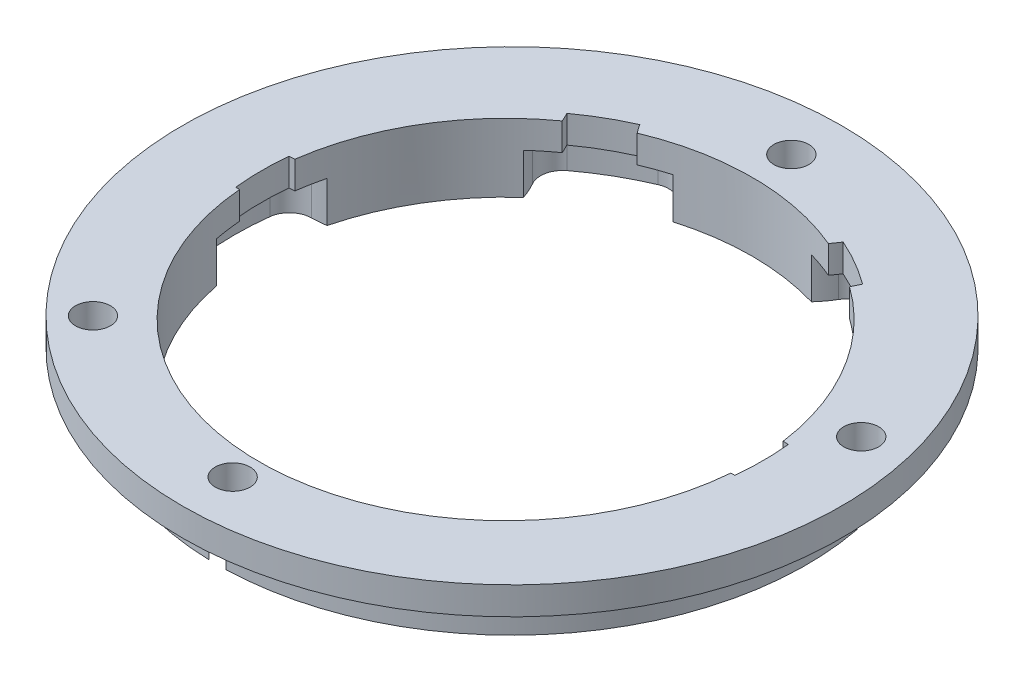
SolidWorks part; units mm, degrees
ref_plane "Front Plane" through (0, 0, 0) normal (0, 0, 1) x (1, 0, 0)
ref_plane "Top Plane" through (0, 0, 0) normal (0, 1, 0) x (1, 0, 0)
ref_plane "Right Plane" through (0, 0, 0) normal (1, 0, 0) x (0, 0, -1)
sketch "Sketch1" plane through (0, 0, 0) normal (0, 1, 0) x (1, 0, 0)
  circle A0 centre (0, 0) radius 31.75 construction
  arc A1 (-10.16, 30.0805) -> (10.16, 30.0805) centre (0, 33.6183) ccw
  arc A2 (20.9705, 23.8391) -> (31.1305, 6.2414) centre (29.1143, 16.8092) ccw
  arc A3 (31.1305, -6.2414) -> (20.9705, -23.8391) centre (29.1143, -16.8092) ccw
  arc A4 (10.16, -30.0805) -> (-10.16, -30.0805) centre (0, -33.6183) ccw
  arc A5 (-20.9705, -23.8391) -> (-31.1305, -6.2414) centre (-29.1143, -16.8092) ccw
  arc A6 (-31.1305, 6.2414) -> (-20.9705, 23.8391) centre (-29.1143, 16.8092) ccw
  arc A7 (-20.9705, 23.8391) -> (-10.16, 30.0805) centre (0, 0) cw
  arc A8 (10.16, 30.0805) -> (20.9705, 23.8391) centre (0, 0) cw
  arc A9 (31.1305, 6.2414) -> (31.1305, -6.2414) centre (0, 0) cw
  arc A10 (20.9705, -23.8391) -> (10.16, -30.0805) centre (0, 0) cw
  arc A11 (-10.16, -30.0805) -> (-20.9705, -23.8391) centre (0, 0) cw
  arc A12 (-31.1305, -6.2414) -> (-31.1305, 6.2414) centre (0, 0) cw
  circle A13 centre (0, 0) radius 6.35
  point P24 (0, 0)
  dimension "D1" = 63.5
  dimension "D3" = 8.89
  dimension "D5" = 12.7
  dimension "D2" = 20.32
  dimension "D4" = 6
extrude "Boss-Extrude1" add sketch "Sketch1" along normal blind 9.652
fillet "Fillet1" radius 2.54 12 edges at (20.9705, 4.826, 23.8391) (31.1305, 4.826, 6.2414) (31.1305, 4.826, -6.2414) (20.9705, 4.826, -23.8391) (10.16, 4.826, -30.0805) (-10.16, 4.826, -30.0805) (-20.9705, 4.826, -23.8391) (-31.1305, 4.826, -6.2414) (-31.1305, 4.826, 6.2414) (-20.9705, 4.826, 23.8391) (10.16, 4.826, 30.0805) (-10.16, 4.826, 30.0805)
sketch "Sketch2" plane through (0, 0, 0) normal (0, -1, 0) x (1, 0, 0)
  circle A0 centre (0, 0) radius 33.75
  arc A24 (19.7507, 22.1068) -> (29.0204, 6.0512) centre (29.1143, 16.8092) ccw
  arc A25 (19.7507, 22.1068) -> (19.0652, 25.3886) centre (17.54, 23.3575) ccw
  arc A26 (19.0652, 25.3886) -> (12.4545, 29.2053) centre (0, 0) ccw
  arc A27 (12.4545, 29.2053) -> (9.2697, 28.158) centre (11.4582, 26.8688) ccw
  arc A28 (-9.2697, 28.158) -> (9.2697, 28.158) centre (0, 33.6183) ccw
  arc A29 (-9.2697, 28.158) -> (-12.4545, 29.2053) centre (-11.4582, 26.8688) ccw
  arc A30 (-12.4545, 29.2053) -> (-19.0652, 25.3886) centre (0, 0) ccw
  arc A31 (-19.0652, 25.3886) -> (-19.7507, 22.1068) centre (-17.54, 23.3575) ccw
  arc A32 (-29.0204, 6.0512) -> (-19.7507, 22.1068) centre (-29.1143, 16.8092) ccw
  arc A33 (-29.0204, 6.0512) -> (-31.5198, 3.8167) centre (-28.9982, 3.5113) ccw
  arc A34 (-31.5198, 3.8167) -> (-31.5198, -3.8167) centre (0, 0) ccw
  arc A35 (-31.5198, -3.8167) -> (-29.0204, -6.0512) centre (-28.9982, -3.5113) ccw
  arc A36 (-19.7507, -22.1068) -> (-29.0204, -6.0512) centre (-29.1143, -16.8092) ccw
  arc A37 (-19.7507, -22.1068) -> (-19.0652, -25.3886) centre (-17.54, -23.3575) ccw
  arc A38 (-19.0652, -25.3886) -> (-12.4545, -29.2053) centre (0, 0) ccw
  arc A39 (-12.4545, -29.2053) -> (-9.2697, -28.158) centre (-11.4582, -26.8688) ccw
  arc A40 (9.2697, -28.158) -> (-9.2697, -28.158) centre (0, -33.6183) ccw
  arc A41 (9.2697, -28.158) -> (12.4545, -29.2053) centre (11.4582, -26.8688) ccw
  arc A42 (12.4545, -29.2053) -> (19.0652, -25.3886) centre (0, 0) ccw
  arc A43 (19.0652, -25.3886) -> (19.7507, -22.1068) centre (17.54, -23.3575) ccw
  arc A44 (29.0204, -6.0512) -> (19.7507, -22.1068) centre (29.1143, -16.8092) ccw
  arc A45 (29.0204, -6.0512) -> (31.5198, -3.8167) centre (28.9982, -3.5113) ccw
  arc A46 (31.5198, -3.8167) -> (31.5198, 3.8167) centre (0, 0) ccw
  arc A47 (31.5198, 3.8167) -> (29.0204, 6.0512) centre (28.9982, 3.5113) ccw
  arc A48 (19.7507, 22.1068) -> (29.0204, 6.0512) centre (29.1143, 16.8092) ccw
  arc A49 (19.7507, 22.1068) -> (19.0652, 25.3886) centre (17.54, 23.3575) ccw
  arc A50 (19.0652, 25.3886) -> (12.4545, 29.2053) centre (0, 0) ccw
  arc A51 (12.4545, 29.2053) -> (9.2697, 28.158) centre (11.4582, 26.8688) ccw
  arc A52 (-9.2697, 28.158) -> (9.2697, 28.158) centre (0, 33.6183) ccw
  arc A53 (-9.2697, 28.158) -> (-12.4545, 29.2053) centre (-11.4582, 26.8688) ccw
  arc A54 (-12.4545, 29.2053) -> (-19.0652, 25.3886) centre (0, 0) ccw
  arc A55 (-19.0652, 25.3886) -> (-19.7507, 22.1068) centre (-17.54, 23.3575) ccw
  arc A56 (-29.0204, 6.0512) -> (-19.7507, 22.1068) centre (-29.1143, 16.8092) ccw
  arc A57 (-29.0204, 6.0512) -> (-31.5198, 3.8167) centre (-28.9982, 3.5113) ccw
  arc A58 (-31.5198, 3.8167) -> (-31.5198, -3.8167) centre (0, 0) ccw
  arc A59 (-31.5198, -3.8167) -> (-29.0204, -6.0512) centre (-28.9982, -3.5113) ccw
  arc A60 (-19.7507, -22.1068) -> (-29.0204, -6.0512) centre (-29.1143, -16.8092) ccw
  arc A61 (-19.7507, -22.1068) -> (-19.0652, -25.3886) centre (-17.54, -23.3575) ccw
  arc A62 (-19.0652, -25.3886) -> (-12.4545, -29.2053) centre (0, 0) ccw
  arc A63 (-12.4545, -29.2053) -> (-9.2697, -28.158) centre (-11.4582, -26.8688) ccw
  arc A64 (9.2697, -28.158) -> (-9.2697, -28.158) centre (0, -33.6183) ccw
  arc A65 (9.2697, -28.158) -> (12.4545, -29.2053) centre (11.4582, -26.8688) ccw
  arc A66 (12.4545, -29.2053) -> (19.0652, -25.3886) centre (0, 0) ccw
  arc A67 (19.0652, -25.3886) -> (19.7507, -22.1068) centre (17.54, -23.3575) ccw
  arc A68 (29.0204, -6.0512) -> (19.7507, -22.1068) centre (29.1143, -16.8092) ccw
  arc A69 (29.0204, -6.0512) -> (31.5198, -3.8167) centre (28.9982, -3.5113) ccw
  arc A70 (31.5198, -3.8167) -> (31.5198, 3.8167) centre (0, 0) ccw
  arc A71 (31.5198, 3.8167) -> (29.0204, 6.0512) centre (28.9982, 3.5113) ccw
  dimension "D2" = 2
  dimension "D1" = 0
extrude "Boss-Extrude2" add sketch "Sketch2" against normal through all separate body
sketch "Sketch3" plane through (0, 9.652, 0) normal (0, 1, 0) x (1, 0, 0)
  arc A24 (12.4545, -29.2053) -> (19.0652, -25.3886) centre (0, 0) ccw
  arc A25 (19.0652, -25.3886) -> (19.7507, -22.1068) centre (17.54, -23.3575) ccw
  arc A26 (29.0204, -6.0512) -> (19.7507, -22.1068) centre (29.1143, -16.8092) ccw
  arc A27 (29.0204, -6.0512) -> (31.5198, -3.8167) centre (28.9982, -3.5113) ccw
  arc A28 (31.5198, -3.8167) -> (31.5198, 3.8167) centre (0, 0) ccw
  arc A29 (31.5198, 3.8167) -> (29.0204, 6.0512) centre (28.9982, 3.5113) ccw
  arc A30 (19.7507, 22.1068) -> (29.0204, 6.0512) centre (29.1143, 16.8092) ccw
  arc A31 (19.7507, 22.1068) -> (19.0652, 25.3886) centre (17.54, 23.3575) ccw
  arc A32 (19.0652, 25.3886) -> (12.4545, 29.2053) centre (0, 0) ccw
  arc A33 (12.4545, 29.2053) -> (9.2697, 28.158) centre (11.4582, 26.8688) ccw
  arc A34 (-9.2697, 28.158) -> (9.2697, 28.158) centre (0, 33.6183) ccw
  arc A35 (-9.2697, 28.158) -> (-12.4545, 29.2053) centre (-11.4582, 26.8688) ccw
  arc A36 (-12.4545, 29.2053) -> (-19.0652, 25.3886) centre (0, 0) ccw
  arc A37 (-19.0652, 25.3886) -> (-19.7507, 22.1068) centre (-17.54, 23.3575) ccw
  arc A38 (-29.0204, 6.0512) -> (-19.7507, 22.1068) centre (-29.1143, 16.8092) ccw
  arc A39 (-29.0204, 6.0512) -> (-31.5198, 3.8167) centre (-28.9982, 3.5113) ccw
  arc A40 (-31.5198, 3.8167) -> (-31.5198, -3.8167) centre (0, 0) ccw
  arc A41 (-31.5198, -3.8167) -> (-29.0204, -6.0512) centre (-28.9982, -3.5113) ccw
  arc A42 (-19.7507, -22.1068) -> (-29.0204, -6.0512) centre (-29.1143, -16.8092) ccw
  arc A43 (-19.7507, -22.1068) -> (-19.0652, -25.3886) centre (-17.54, -23.3575) ccw
  arc A44 (-19.0652, -25.3886) -> (-12.4545, -29.2053) centre (0, 0) ccw
  arc A45 (-12.4545, -29.2053) -> (-9.2697, -28.158) centre (-11.4582, -26.8688) ccw
  arc A46 (9.2697, -28.158) -> (-9.2697, -28.158) centre (0, -33.6183) ccw
  arc A47 (9.2697, -28.158) -> (12.4545, -29.2053) centre (11.4582, -26.8688) ccw
  arc A48 (12.4545, -29.2053) -> (19.0652, -25.3886) centre (0, 0) ccw
  arc A49 (19.0652, -25.3886) -> (19.7507, -22.1068) centre (17.54, -23.3575) ccw
  arc A50 (29.0204, -6.0512) -> (19.7507, -22.1068) centre (29.1143, -16.8092) ccw
  arc A51 (29.0204, -6.0512) -> (31.5198, -3.8167) centre (28.9982, -3.5113) ccw
  arc A52 (31.5198, -3.8167) -> (31.5198, 3.8167) centre (0, 0) ccw
  arc A53 (31.5198, 3.8167) -> (29.0204, 6.0512) centre (28.9982, 3.5113) ccw
  arc A54 (19.7507, 22.1068) -> (29.0204, 6.0512) centre (29.1143, 16.8092) ccw
  arc A55 (19.7507, 22.1068) -> (19.0652, 25.3886) centre (17.54, 23.3575) ccw
  arc A56 (19.0652, 25.3886) -> (12.4545, 29.2053) centre (0, 0) ccw
  arc A57 (12.4545, 29.2053) -> (9.2697, 28.158) centre (11.4582, 26.8688) ccw
  arc A58 (-9.2697, 28.158) -> (9.2697, 28.158) centre (0, 33.6183) ccw
  arc A59 (-9.2697, 28.158) -> (-12.4545, 29.2053) centre (-11.4582, 26.8688) ccw
  arc A60 (-12.4545, 29.2053) -> (-19.0652, 25.3886) centre (0, 0) ccw
  arc A61 (-19.0652, 25.3886) -> (-19.7507, 22.1068) centre (-17.54, 23.3575) ccw
  arc A62 (-29.0204, 6.0512) -> (-19.7507, 22.1068) centre (-29.1143, 16.8092) ccw
  arc A63 (-29.0204, 6.0512) -> (-31.5198, 3.8167) centre (-28.9982, 3.5113) ccw
  arc A64 (-31.5198, 3.8167) -> (-31.5198, -3.8167) centre (0, 0) ccw
  arc A65 (-31.5198, -3.8167) -> (-29.0204, -6.0512) centre (-28.9982, -3.5113) ccw
  arc A66 (-19.7507, -22.1068) -> (-29.0204, -6.0512) centre (-29.1143, -16.8092) ccw
  arc A67 (-19.7507, -22.1068) -> (-19.0652, -25.3886) centre (-17.54, -23.3575) ccw
  arc A68 (-19.0652, -25.3886) -> (-12.4545, -29.2053) centre (0, 0) ccw
  arc A69 (-12.4545, -29.2053) -> (-9.2697, -28.158) centre (-11.4582, -26.8688) ccw
  arc A70 (9.2697, -28.158) -> (-9.2697, -28.158) centre (0, -33.6183) ccw
  arc A71 (9.2697, -28.158) -> (12.4545, -29.2053) centre (11.4582, -26.8688) ccw
  dimension "D1" = 0
extrude "Cut-Extrude1" cut sketch "Sketch3" against normal through all
sketch "Sketch4" plane through (0, 9.652, 0) normal (0, 1, 0) x (1, 0, 0)
  circle A0 centre (0, 0) radius 37.75
  circle A1 centre (0, 0) radius 33.75
  circle A2 centre (0, 0) radius 33.75 construction
  arc A26 (9.2697, -28.158) -> (-9.2697, -28.158) centre (0, -33.6183) ccw
  arc A27 (9.2697, -28.158) -> (12.4545, -29.2053) centre (11.4582, -26.8688) ccw
  arc A28 (12.4545, -29.2053) -> (19.0652, -25.3886) centre (0, 0) ccw
  arc A29 (19.0652, -25.3886) -> (19.7507, -22.1068) centre (17.54, -23.3575) ccw
  arc A30 (29.0204, -6.0512) -> (19.7507, -22.1068) centre (29.1143, -16.8092) ccw
  arc A31 (29.0204, -6.0512) -> (31.5198, -3.8167) centre (28.9982, -3.5113) ccw
  arc A32 (31.5198, -3.8167) -> (31.5198, 3.8167) centre (0, 0) ccw
  arc A33 (31.5198, 3.8167) -> (29.0204, 6.0512) centre (28.9982, 3.5113) ccw
  arc A34 (19.7507, 22.1068) -> (29.0204, 6.0512) centre (29.1143, 16.8092) ccw
  arc A35 (19.7507, 22.1068) -> (19.0652, 25.3886) centre (17.54, 23.3575) ccw
  arc A36 (19.0652, 25.3886) -> (12.4545, 29.2053) centre (0, 0) ccw
  arc A37 (12.4545, 29.2053) -> (9.2697, 28.158) centre (11.4582, 26.8688) ccw
  arc A38 (-9.2697, 28.158) -> (9.2697, 28.158) centre (0, 33.6183) ccw
  arc A39 (-9.2697, 28.158) -> (-12.4545, 29.2053) centre (-11.4582, 26.8688) ccw
  arc A40 (-12.4545, 29.2053) -> (-19.0652, 25.3886) centre (0, 0) ccw
  arc A41 (-19.0652, 25.3886) -> (-19.7507, 22.1068) centre (-17.54, 23.3575) ccw
  arc A42 (-29.0204, 6.0512) -> (-19.7507, 22.1068) centre (-29.1143, 16.8092) ccw
  arc A43 (-29.0204, 6.0512) -> (-31.5198, 3.8167) centre (-28.9982, 3.5113) ccw
  arc A44 (-31.5198, 3.8167) -> (-31.5198, -3.8167) centre (0, 0) ccw
  arc A45 (-31.5198, -3.8167) -> (-29.0204, -6.0512) centre (-28.9982, -3.5113) ccw
  arc A46 (-19.7507, -22.1068) -> (-29.0204, -6.0512) centre (-29.1143, -16.8092) ccw
  arc A47 (-19.7507, -22.1068) -> (-19.0652, -25.3886) centre (-17.54, -23.3575) ccw
  arc A48 (-19.0652, -25.3886) -> (-12.4545, -29.2053) centre (0, 0) ccw
  arc A49 (-12.4545, -29.2053) -> (-9.2697, -28.158) centre (-11.4582, -26.8688) ccw
  arc A50 (9.2697, -28.158) -> (-9.2697, -28.158) centre (0, -33.6183) ccw
  arc A51 (9.2697, -28.158) -> (12.4545, -29.2053) centre (11.4582, -26.8688) ccw
  arc A52 (12.4545, -29.2053) -> (19.0652, -25.3886) centre (0, 0) ccw
  arc A53 (19.0652, -25.3886) -> (19.7507, -22.1068) centre (17.54, -23.3575) ccw
  arc A54 (29.0204, -6.0512) -> (19.7507, -22.1068) centre (29.1143, -16.8092) ccw
  arc A55 (29.0204, -6.0512) -> (31.5198, -3.8167) centre (28.9982, -3.5113) ccw
  arc A56 (31.5198, -3.8167) -> (31.5198, 3.8167) centre (0, 0) ccw
  arc A57 (31.5198, 3.8167) -> (29.0204, 6.0512) centre (28.9982, 3.5113) ccw
  arc A58 (19.7507, 22.1068) -> (29.0204, 6.0512) centre (29.1143, 16.8092) ccw
  arc A59 (19.7507, 22.1068) -> (19.0652, 25.3886) centre (17.54, 23.3575) ccw
  arc A60 (19.0652, 25.3886) -> (12.4545, 29.2053) centre (0, 0) ccw
  arc A61 (12.4545, 29.2053) -> (9.2697, 28.158) centre (11.4582, 26.8688) ccw
  arc A62 (-9.2697, 28.158) -> (9.2697, 28.158) centre (0, 33.6183) ccw
  arc A63 (-9.2697, 28.158) -> (-12.4545, 29.2053) centre (-11.4582, 26.8688) ccw
  arc A64 (-12.4545, 29.2053) -> (-19.0652, 25.3886) centre (0, 0) ccw
  arc A65 (-19.0652, 25.3886) -> (-19.7507, 22.1068) centre (-17.54, 23.3575) ccw
  arc A66 (-29.0204, 6.0512) -> (-19.7507, 22.1068) centre (-29.1143, 16.8092) ccw
  arc A67 (-29.0204, 6.0512) -> (-31.5198, 3.8167) centre (-28.9982, 3.5113) ccw
  arc A68 (-31.5198, 3.8167) -> (-31.5198, -3.8167) centre (0, 0) ccw
  arc A69 (-31.5198, -3.8167) -> (-29.0204, -6.0512) centre (-28.9982, -3.5113) ccw
  arc A70 (-19.7507, -22.1068) -> (-29.0204, -6.0512) centre (-29.1143, -16.8092) ccw
  arc A71 (-19.7507, -22.1068) -> (-19.0652, -25.3886) centre (-17.54, -23.3575) ccw
  arc A72 (-19.0652, -25.3886) -> (-12.4545, -29.2053) centre (0, 0) ccw
  arc A73 (-12.4545, -29.2053) -> (-9.2697, -28.158) centre (-11.4582, -26.8688) ccw
  arc M27 (29.0204, -6.0512) -> (19.7507, -22.1068) centre (29.1143, -16.8092) ccw
  arc M28 (19.7507, -22.1068) -> (19.0652, -25.3886) centre (17.54, -23.3575) cw
  arc M29 (19.0652, -25.3886) -> (12.4545, -29.2053) centre (0, 0) cw
  arc M30 (12.4545, -29.2053) -> (9.2697, -28.158) centre (11.4582, -26.8688) cw
  arc M31 (9.2697, -28.158) -> (-9.2697, -28.158) centre (0, -33.6183) ccw
  arc M32 (-9.2697, -28.158) -> (-12.4545, -29.2053) centre (-11.4582, -26.8688) cw
  arc M33 (-12.4545, -29.2053) -> (-19.0652, -25.3886) centre (0, 0) cw
  arc M34 (-19.0652, -25.3886) -> (-19.7507, -22.1068) centre (-17.54, -23.3575) cw
  arc M35 (-19.7507, -22.1068) -> (-29.0204, -6.0512) centre (-29.1143, -16.8092) ccw
  arc M36 (-29.0204, -6.0512) -> (-31.5198, -3.8167) centre (-28.9982, -3.5113) cw
  arc M37 (-31.5198, -3.8167) -> (-31.5198, 3.8167) centre (0, 0) cw
  arc M38 (-31.5198, 3.8167) -> (-29.0204, 6.0512) centre (-28.9982, 3.5113) cw
  arc M39 (-29.0204, 6.0512) -> (-19.7507, 22.1068) centre (-29.1143, 16.8092) ccw
  arc M40 (-19.7507, 22.1068) -> (-19.0652, 25.3886) centre (-17.54, 23.3575) cw
  arc M41 (-19.0652, 25.3886) -> (-12.4545, 29.2053) centre (0, 0) cw
  arc M42 (-12.4545, 29.2053) -> (-9.2697, 28.158) centre (-11.4582, 26.8688) cw
  arc M43 (-9.2697, 28.158) -> (9.2697, 28.158) centre (0, 33.6183) ccw
  arc M44 (9.2697, 28.158) -> (12.4545, 29.2053) centre (11.4582, 26.8688) cw
  arc M45 (12.4545, 29.2053) -> (19.0652, 25.3886) centre (0, 0) cw
  arc M46 (19.0652, 25.3886) -> (19.7507, 22.1068) centre (17.54, 23.3575) cw
  arc M47 (19.7507, 22.1068) -> (29.0204, 6.0512) centre (29.1143, 16.8092) ccw
  arc M48 (29.0204, 6.0512) -> (31.5198, 3.8167) centre (28.9982, 3.5113) cw
  arc M49 (31.5198, 3.8167) -> (31.5198, -3.8167) centre (0, 0) cw
  arc M50 (31.5198, -3.8167) -> (29.0204, -6.0512) centre (28.9982, -3.5113) cw
  circle M51 centre (0, 0) radius 33.75
  dimension "D3" = 4
  dimension "D1" = 0
  dimension "D2" = 0
extrude "Boss-Extrude3" add sketch "Sketch4" along normal blind 3.175 contours M51 M50 M27 M28 M29 M30 M31 M32 M33 M34 M35 M36 M37 M38 M39 M40 M41 M42 M43 M44 M45 M46 M47 M48 M49 | A0 M51
sketch "Sketch9" plane through (0, 12.827, 0) normal (0, 1, 0) x (1, 0, 0)
  arc A0 (-19.0652, 25.3886) -> (-19.7507, 22.1068) centre (-17.54, 23.3575) ccw construction
  arc A1 (-29.0204, 6.0512) -> (-19.7507, 22.1068) centre (-29.1143, 16.8092) ccw construction
  arc A2 (-29.0204, 6.0512) -> (-31.5198, 3.8167) centre (-28.9982, 3.5113) ccw construction
  arc A3 (-31.5198, 3.8167) -> (-31.5198, -3.8167) centre (0, 0) ccw construction
  arc A4 (-31.5198, -3.8167) -> (-29.0204, -6.0512) centre (-28.9982, -3.5113) ccw construction
  arc A5 (-19.7507, -22.1068) -> (-29.0204, -6.0512) centre (-29.1143, -16.8092) ccw construction
  arc A6 (-19.7507, -22.1068) -> (-19.0652, -25.3886) centre (-17.54, -23.3575) ccw construction
  arc A7 (-19.0652, -25.3886) -> (-12.4545, -29.2053) centre (0, 0) ccw construction
  arc A8 (-12.4545, -29.2053) -> (-9.2697, -28.158) centre (-11.4582, -26.8688) ccw construction
  arc A9 (9.2697, -28.158) -> (-9.2697, -28.158) centre (0, -33.6183) ccw construction
  arc A10 (9.2697, -28.158) -> (12.4545, -29.2053) centre (11.4582, -26.8688) ccw construction
  arc A11 (19.0652, -25.3886) -> (19.7507, -22.1068) centre (17.54, -23.3575) ccw construction
  arc A12 (12.4545, -29.2053) -> (19.0652, -25.3886) centre (0, 0) ccw construction
  arc A13 (29.0204, -6.0512) -> (19.7507, -22.1068) centre (29.1143, -16.8092) ccw construction
  arc A14 (29.0204, -6.0512) -> (31.5198, -3.8167) centre (28.9982, -3.5113) ccw construction
  arc A15 (31.5198, -3.8167) -> (31.5198, 3.8167) centre (0, 0) ccw construction
  arc A16 (31.5198, 3.8167) -> (29.0204, 6.0512) centre (28.9982, 3.5113) ccw construction
  arc A17 (19.7507, 22.1068) -> (29.0204, 6.0512) centre (29.1143, 16.8092) ccw construction
  arc A18 (19.7507, 22.1068) -> (19.0652, 25.3886) centre (17.54, 23.3575) ccw construction
  arc A19 (19.0652, 25.3886) -> (12.4545, 29.2053) centre (0, 0) ccw construction
  arc A20 (12.4545, 29.2053) -> (9.2697, 28.158) centre (11.4582, 26.8688) ccw construction
  arc A21 (-9.2697, 28.158) -> (9.2697, 28.158) centre (0, 33.6183) ccw construction
  arc A22 (-9.2697, 28.158) -> (-12.4545, 29.2053) centre (-11.4582, 26.8688) ccw construction
  arc A23 (-12.4545, 29.2053) -> (-19.0652, 25.3886) centre (0, 0) ccw construction
  arc A24 (-19.0652, 25.3886) -> (-19.7507, 22.1068) centre (-17.54, 23.3575) ccw
  arc A25 (-29.0204, 6.0512) -> (-19.7507, 22.1068) centre (-29.1143, 16.8092) ccw
  arc A26 (-29.0204, 6.0512) -> (-31.5198, 3.8167) centre (-28.9982, 3.5113) ccw
  arc A27 (-31.5198, 3.8167) -> (-31.5198, -3.8167) centre (0, 0) ccw
  arc A28 (-31.5198, -3.8167) -> (-29.0204, -6.0512) centre (-28.9982, -3.5113) ccw
  arc A29 (-19.7507, -22.1068) -> (-29.0204, -6.0512) centre (-29.1143, -16.8092) ccw
  arc A30 (-19.7507, -22.1068) -> (-19.0652, -25.3886) centre (-17.54, -23.3575) ccw
  arc A31 (-19.0652, -25.3886) -> (-12.4545, -29.2053) centre (0, 0) ccw
  arc A32 (-12.4545, -29.2053) -> (-9.2697, -28.158) centre (-11.4582, -26.8688) ccw
  arc A33 (9.2697, -28.158) -> (-9.2697, -28.158) centre (0, -33.6183) ccw
  arc A34 (9.2697, -28.158) -> (12.4545, -29.2053) centre (11.4582, -26.8688) ccw
  arc A35 (19.0652, -25.3886) -> (19.7507, -22.1068) centre (17.54, -23.3575) ccw
  arc A36 (12.4545, -29.2053) -> (19.0652, -25.3886) centre (0, 0) ccw
  arc A37 (29.0204, -6.0512) -> (19.7507, -22.1068) centre (29.1143, -16.8092) ccw
  arc A38 (29.0204, -6.0512) -> (31.5198, -3.8167) centre (28.9982, -3.5113) ccw
  arc A39 (31.5198, -3.8167) -> (31.5198, 3.8167) centre (0, 0) ccw
  arc A40 (31.5198, 3.8167) -> (29.0204, 6.0512) centre (28.9982, 3.5113) ccw
  arc A41 (19.7507, 22.1068) -> (29.0204, 6.0512) centre (29.1143, 16.8092) ccw
  arc A42 (19.7507, 22.1068) -> (19.0652, 25.3886) centre (17.54, 23.3575) ccw
  arc A43 (19.0652, 25.3886) -> (12.4545, 29.2053) centre (0, 0) ccw
  arc A44 (12.4545, 29.2053) -> (9.2697, 28.158) centre (11.4582, 26.8688) ccw
  arc A45 (-9.2697, 28.158) -> (9.2697, 28.158) centre (0, 33.6183) ccw
  arc A46 (-9.2697, 28.158) -> (-12.4545, 29.2053) centre (-11.4582, 26.8688) ccw
  arc A47 (-12.4545, 29.2053) -> (-19.0652, 25.3886) centre (0, 0) ccw
  arc A48 (-16.9442, 23.2262) -> (-16.9442, 23.2262) centre (-16.9442, 23.2262) ccw
  arc A49 (-28.5866, 3.061) -> (-16.9442, 23.2262) centre (-29.1143, 16.8092) ccw
  arc A50 (-28.5866, 3.061) -> (-28.5866, 3.061) centre (-28.5866, 3.061) ccw
  arc A51 (-28.5866, 3.061) -> (-28.5866, -3.061) centre (0, 0) ccw
  arc A52 (-28.5866, -3.061) -> (-28.5866, -3.061) centre (-28.5866, -3.061) ccw
  arc A53 (-16.9442, -23.2262) -> (-28.5866, -3.061) centre (-29.1143, -16.8092) ccw
  arc A54 (-16.9442, -23.2262) -> (-16.9442, -23.2262) centre (-16.9442, -23.2262) ccw
  arc A55 (-16.9442, -23.2262) -> (-11.6424, -26.2872) centre (0, 0) ccw
  arc A56 (-11.6424, -26.2872) -> (-11.6424, -26.2872) centre (-11.6424, -26.2872) ccw
  arc A57 (11.6424, -26.2872) -> (-11.6424, -26.2872) centre (0, -33.6183) ccw
  arc A58 (11.6424, -26.2872) -> (11.6424, -26.2872) centre (11.6424, -26.2872) ccw
  arc A59 (11.6424, -26.2872) -> (16.9442, -23.2262) centre (0, 0) ccw
  arc A60 (16.9442, -23.2262) -> (16.9442, -23.2262) centre (16.9442, -23.2262) ccw
  arc A61 (28.5866, -3.061) -> (16.9442, -23.2262) centre (29.1143, -16.8092) ccw
  arc A62 (28.5866, -3.061) -> (28.5866, -3.061) centre (28.5866, -3.061) ccw
  arc A63 (28.5866, -3.061) -> (28.5866, 3.061) centre (0, 0) ccw
  arc A64 (28.5866, 3.061) -> (28.5866, 3.061) centre (28.5866, 3.061) ccw
  arc A65 (16.9442, 23.2262) -> (28.5866, 3.061) centre (29.1143, 16.8092) ccw
  arc A66 (16.9442, 23.2262) -> (16.9442, 23.2262) centre (16.9442, 23.2262) ccw
  arc A67 (16.9442, 23.2262) -> (11.6424, 26.2872) centre (0, 0) ccw
  arc A68 (11.6424, 26.2872) -> (11.6424, 26.2872) centre (11.6424, 26.2872) ccw
  arc A69 (-11.6424, 26.2872) -> (11.6424, 26.2872) centre (0, 33.6183) ccw
  arc A70 (-11.6424, 26.2872) -> (-11.6424, 26.2872) centre (-11.6424, 26.2872) ccw
  arc A71 (-11.6424, 26.2872) -> (-16.9442, 23.2262) centre (0, 0) ccw
  dimension "D1" = 3
extrude "Boss-Extrude4" add sketch "Sketch9" against normal blind 3.15
extrude "Cut-Extrude2" cut sketch "Sketch5" against normal through all
sketch "Sketch5" plane through (-2.8749, 12.827, -4.8237) normal (0, 1, 0) x (1, 0, 0)
  arc A8 (-21.1251, -30.8237) -> (-21.1251, -26.8237) centre (-21.1251, -28.8237) ccw
  arc A9 (-21.1251, -26.8237) -> (-21.1251, -30.8237) centre (-21.1251, -28.8237) ccw
  arc A10 (34.8749, 5.1763) -> (34.8749, 1.1763) centre (34.8749, 3.1763) ccw
  arc A11 (34.8749, 1.1763) -> (34.8749, 5.1763) centre (34.8749, 3.1763) ccw
  arc A12 (2.8749, 29.1763) -> (2.8749, 25.1763) centre (2.8749, 27.1763) ccw
  arc A13 (2.8749, 25.1763) -> (2.8749, 29.1763) centre (2.8749, 27.1763) ccw
  arc A14 (2.8749, -38.8237) -> (2.8749, -34.8237) centre (2.8749, -36.8237) ccw
  arc A15 (2.8749, -34.8237) -> (2.8749, -38.8237) centre (2.8749, -36.8237) ccw
extrude "Cut-Extrude3" cut sketch "Sketch6" against normal through all
sketch "Sketch6" plane through (-2.8749, 12.827, -4.8237) normal (0, 1, 0) x (1, 0, 0)
  circle A0 centre (2.8749, -5.5549) radius 28.2311
sketch "Sketch8" plane through (0, 0, 0) normal (0, -1, 0) x (1, 0, 0)
  arc A8 (-25.2267, 22.4204) -> (-22.4204, 25.2267) centre (-24, 24) ccw
  arc A9 (-25.2267, 22.4204) -> (-0.9943, -33.7354) centre (0, 0) ccw
  arc A10 (0.9943, -33.7354) -> (-0.9943, -33.7354) centre (0, -32) ccw
  arc A11 (0.9943, -33.7354) -> (32.2389, -9.9857) centre (0, 0) ccw
  arc A12 (33.1453, -6.3604) -> (32.2389, -9.9857) centre (32, -8) ccw
  arc A13 (33.1453, -6.3604) -> (0.9943, 33.7354) centre (0, 0) ccw
  arc A14 (-0.9943, 33.7354) -> (0.9943, 33.7354) centre (0, 32) ccw
  arc A15 (-0.9943, 33.7354) -> (-22.4204, 25.2267) centre (0, 0) ccw
  arc A16 (-25.2267, 22.4204) -> (-22.4204, 25.2267) centre (-24, 24) ccw
  arc A17 (-25.2267, 22.4204) -> (-0.9943, -33.7354) centre (0, 0) ccw
  arc A18 (0.9943, -33.7354) -> (-0.9943, -33.7354) centre (0, -32) ccw
  arc A19 (0.9943, -33.7354) -> (32.2389, -9.9857) centre (0, 0) ccw
  arc A20 (33.1453, -6.3604) -> (32.2389, -9.9857) centre (32, -8) ccw
  arc A21 (33.1453, -6.3604) -> (0.9943, 33.7354) centre (0, 0) ccw
  arc A22 (-0.9943, 33.7354) -> (0.9943, 33.7354) centre (0, 32) ccw
  arc A23 (-0.9943, 33.7354) -> (-22.4204, 25.2267) centre (0, 0) ccw
  dimension "D1" = 0
extrude "Cut-Extrude5" cut sketch "Sketch8" against normal blind 5
